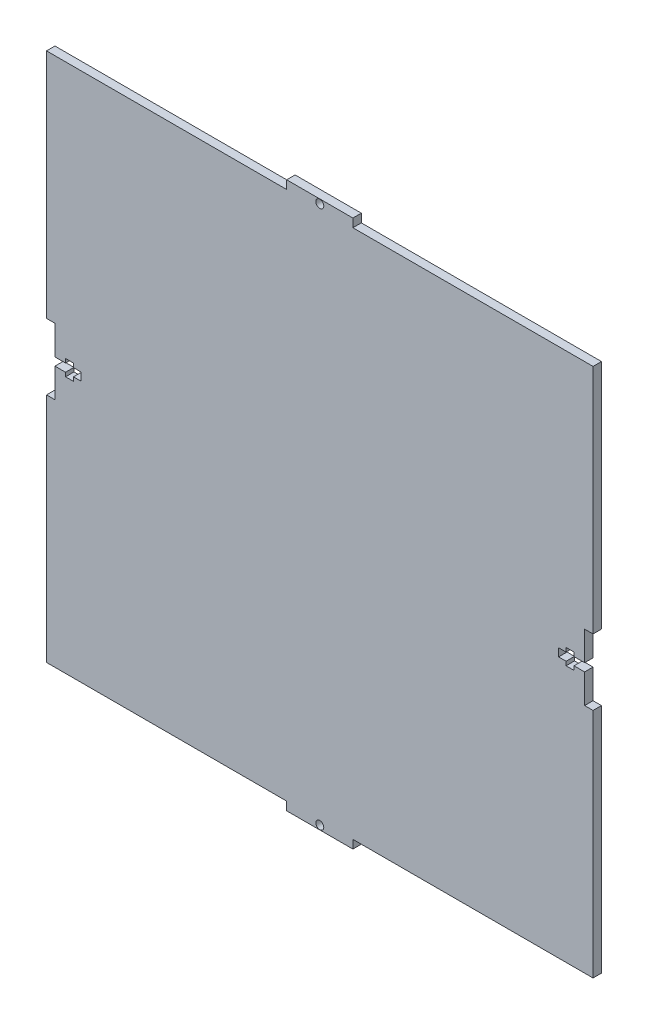
SolidWorks part; units mm, degrees
ref_plane "Front Plane" through (0, 0, 0) normal (0, 0, 1) x (1, 0, 0)
ref_plane "Top Plane" through (0, 0, 0) normal (0, 1, 0) x (1, 0, 0)
ref_plane "Right Plane" through (0, 0, 0) normal (1, 0, 0) x (0, 0, -1)
sketch "Sketch1" plane through (0, 0, 0) normal (0, 0, 1) x (1, 0, 0)
  line L0 (-12.5, 50) -> (12.5, 50) construction
  line L1 (-103.18, 100) -> (-12.5, 100)
  line L2 (-103.18, 100) -> (-103.18, 12.5)
  line L3 (-103.18, -100) -> (-12.5, -100)
  line L4 (103.18, 100) -> (103.18, 12.5)
  line L5 (-103.18, 100) -> (103.18, -100) construction
  line L6 (-103.18, -100) -> (103.18, 100) construction
  line L11 (12.5, 100) -> (12.5, 103.18)
  line L12 (12.5, 103.18) -> (-12.5, 103.18)
  line L17 (-12.5, 100) -> (-12.5, 103.18)
  line L18 (12.5, 100) -> (103.18, 100)
  line L25 (0, 100) -> (0, -100) construction
  line L26 (-100, 0) -> (100, 0) construction
  line L27 (-100, -1.5) -> (-100, -12.5)
  line L28 (-100, 12.5) -> (-103.18, 12.5)
  line L29 (-100, 12.5) -> (-100, 1.5)
  line L30 (-100, -12.5) -> (-103.18, -12.5)
  line L32 (-100, 12.5) -> (-103.18, -12.5) construction
  line L33 (-100, -12.5) -> (-103.18, 12.5) construction
  line L34 (-90.18, 1.5) -> (-93, 1.5)
  line L35 (-90.18, 1.5) -> (-90.18, -1.5)
  line L36 (-90.18, -1.5) -> (-93, -1.5)
  line L38 (-90.18, 1.5) -> (-100, -1.5) construction
  line L39 (-90.18, -1.5) -> (-100, 1.5) construction
  line L44 (-96, 3) -> (-93, 3)
  line L45 (-96, 3) -> (-96, 1.5)
  line L46 (-96, -3) -> (-93, -3)
  line L47 (-93, 3) -> (-93, 1.5)
  line L48 (-96, 3) -> (-93, -3) construction
  line L49 (-96, -3) -> (-93, 3) construction
  line L50 (-96, -1.5) -> (-96, -3)
  line L51 (-93, -1.5) -> (-93, -3)
  line L52 (-96, 1.5) -> (-100, 1.5)
  line L53 (-96, -1.5) -> (-100, -1.5)
  line L54 (90.18, 1.5) -> (93, 1.5)
  line L55 (93, 3) -> (93, 1.5)
  line L56 (96, 3) -> (93, 3)
  line L57 (96, 3) -> (96, 1.5)
  line L58 (96, 1.5) -> (100, 1.5)
  line L59 (100, 12.5) -> (100, 1.5)
  line L60 (100, 12.5) -> (103.18, 12.5)
  line L62 (100, -12.5) -> (103.18, -12.5)
  line L63 (100, -1.5) -> (100, -12.5)
  line L64 (96, -1.5) -> (100, -1.5)
  line L65 (96, -1.5) -> (96, -3)
  line L66 (96, -3) -> (93, -3)
  line L67 (93, -1.5) -> (93, -3)
  line L68 (90.18, -1.5) -> (93, -1.5)
  line L69 (90.18, 1.5) -> (90.18, -1.5)
  line L70 (-103.18, -12.5) -> (-103.18, -100)
  line L71 (103.18, -12.5) -> (103.18, -100)
  line L72 (0, -103.18) -> (0, -100) construction
  line L74 (12.5, -100) -> (12.5, -103.18)
  line L75 (12.5, -103.18) -> (-12.5, -103.18)
  line L76 (-12.5, -100) -> (-12.5, -103.18)
  line L77 (12.5, -101.59) -> (-12.5, -101.59) construction
  line L78 (12.5, -100) -> (103.18, -100)
  circle A2 centre (0, -101.59) radius 1.5
  circle A3 centre (0, 101.59) radius 1.5
  point P0 (0, 0)
  point P6 (-50, 50)
  point P11 (50, 50)
  point P16 (0, 0)
  point P27 (0, 50)
  point P30 (-101.59, 0)
  point P35 (-95.09, 0)
  point P40 (-95.09, 0)
  point P41 (-94.5, 0)
  dimension "D13" = 25
  dimension "D23" = 3
  dimension "D1" = 200
  dimension "D2" = 206.36
  dimension "D3" = 6
  dimension "D9" = 50
  dimension "D10" = 50
  dimension "D14" = 50
  dimension "D15" = 25
  dimension "D16" = 13
  dimension "D17" = 3.18
  dimension "D18" = 3
  dimension "D19" = 4
  dimension "D20" = 3
  dimension "D21" = 3.18
  dimension "D22" = 25
extrude "Boss-Extrude1" add sketch "Sketch1" along normal blind 3.18
